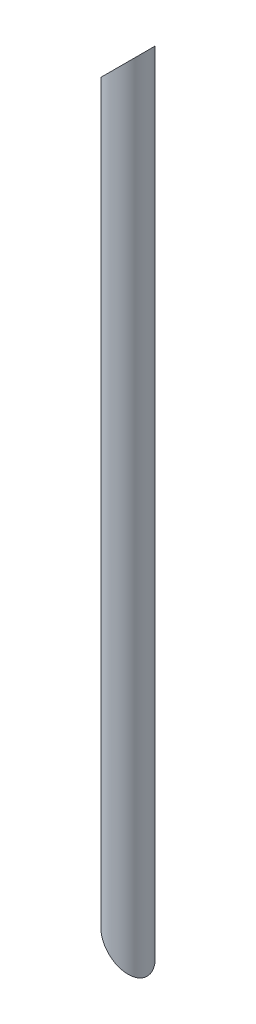
SolidWorks part; units mm, degrees
ref_plane "Plano frontal" through (0, 0, 0) normal (0, 0, 1) x (1, 0, 0)
ref_plane "Plano superior" through (0, 0, 0) normal (0, 1, 0) x (1, 0, 0)
ref_plane "Plano direito" through (0, 0, 0) normal (1, 0, 0) x (0, 0, -1)
sketch "Esboço2" plane through (0, 0, 0) normal (0, 0, 1) x (1, 0, 0)
  line L0 (0, 0) -> (0, 1640) construction
  line L1 (39.3, 0) -> (39.3, 1640)
  line L2 (39.3, 1640) -> (0, 1640)
  line L3 (39.3, 0) -> (0, 0)
  line L4 (0, 0) -> (0, 1640)
  dimension "D1" = 39.3
  dimension "D2" = 1640
revolve "Revolução2" add sketch "Esboço2" angle 360 about L0
sketch "Esboço3" plane through (0, 0, 0) normal (0, 0, 1) x (1, 0, 0)
  line L0 (-39.3, 1640) -> (39.3, 1640)
  line L1 (39.3, 1640) -> (-39.3, 1561.4)
  line L2 (-39.3, 1640) -> (-39.3, 0) construction
  line L3 (-39.3, 1561.4) -> (-39.3, 1640)
  line L4 (39.3, 0) -> (-39.3, 78.6)
  line L8 (-39.3, 78.6) -> (-39.3, 0)
  line L9 (-39.3, 0) -> (39.3, 0)
extrude "Corte-extrusão1" cut sketch "Esboço3" against normal through all both and the other way through all
sketch "Esboço9" plane through (0, 0, 0) normal (0, 1, 0) x (1, 0, 0)
  circle A0 centre (0, 0) radius 35.8738
extrude "Corte-extrusão6" cut sketch "Esboço9" along normal through all
